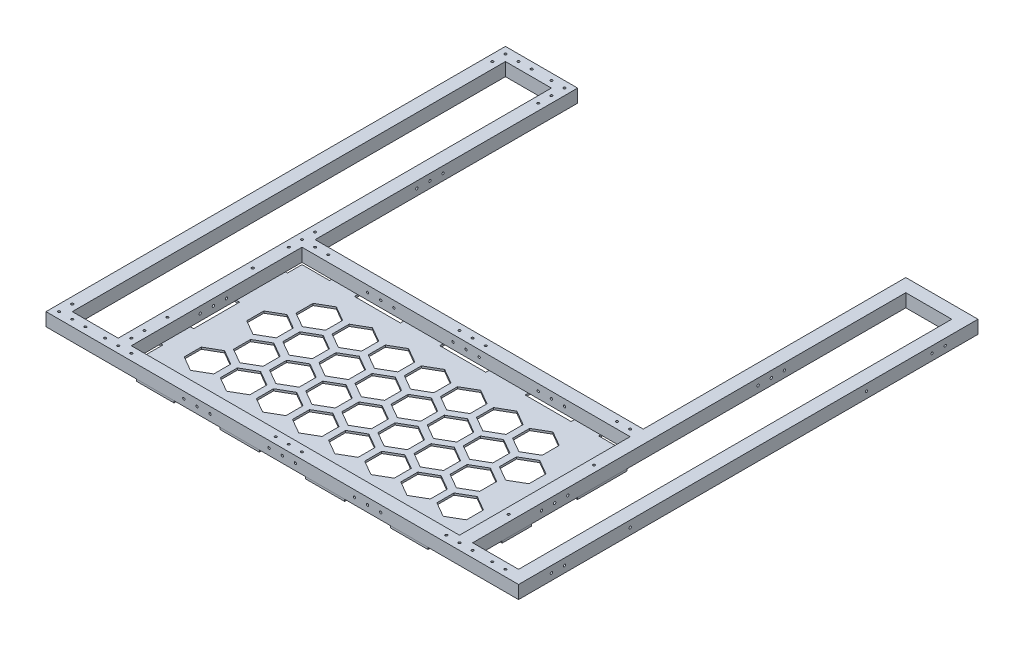
SolidWorks part; units mm, degrees
ref_plane "前视基准面" through (0, 0, 0) normal (0, 0, 1) x (1, 0, 0)
ref_plane "上视基准面" through (0, 0, 0) normal (0, 1, 0) x (1, 0, 0)
ref_plane "右视基准面" through (0, 0, 0) normal (1, 0, 0) x (0, 0, -1)
sketch "草图1" plane through (0, 0, 0) normal (0, 1, 0) x (1, 0, 0)
  line L0 (0, 0) -> (0, 100.2778) construction
  line L1 (250, 10) -> (-250, 10)
  line L2 (250, 10) -> (250, -10)
  line L3 (250, -10) -> (-250, -10)
  line L4 (-250, 10) -> (-250, -10)
  line L5 (250, 10) -> (-250, -10) construction
  line L6 (250, -10) -> (-250, 10) construction
  line L7 (360, 390) -> (250, 390)
  line L8 (-360, -270) -> (360, -270)
  line L9 (-360, -270) -> (-360, -290)
  line L10 (-360, -290) -> (360, -290)
  line L11 (360, -270) -> (360, -290)
  line L12 (-340, -270) -> (-360, -270)
  line L13 (-340, -270) -> (-340, 390)
  line L14 (-340, 390) -> (-360, 390)
  line L15 (-360, -270) -> (-360, 390)
  line L16 (-360, 410) -> (-250, 410)
  line L17 (-360, 410) -> (-360, 390)
  line L18 (-360, 390) -> (-250, 390)
  line L19 (-250, 410) -> (-250, 390)
  line L20 (-270, 390) -> (-250, 390)
  line L21 (-270, 390) -> (-270, -270)
  line L22 (-270, -270) -> (-250, -270)
  line L23 (-250, 390) -> (-250, -270)
  line L24 (250, 410) -> (250, 390)
  line L25 (340, -270) -> (360, -270)
  line L26 (360, 410) -> (250, 410)
  line L31 (270, -270) -> (250, -270)
  line L32 (250, 390) -> (250, -270)
  line L33 (270, 390) -> (250, 390)
  line L34 (270, 390) -> (270, -270)
  line L35 (360, 410) -> (360, 390)
  line L36 (340, 390) -> (360, 390)
  line L38 (340, -270) -> (360, -270)
  line L39 (340, 390) -> (360, 390)
  line L40 (340, 390) -> (340, -270)
  line L41 (340, -270) -> (360, -270)
  line L42 (360, 390) -> (360, -270)
  point P0 (0, 0)
  dimension "D1" = 20
  dimension "D2" = 20
  dimension "D3" = 20
  dimension "D4" = 20
  dimension "D5" = 20
  dimension "D6" = 110
  dimension "D7" = 700
  dimension "D8" = 720
  dimension "D9" = 400
extrude "凸台-拉伸1" add sketch "草图1" along normal blind 20 contours L23 L18 L21 L8 L4 | L19 L16 L17 L14 L18 | L15 L8 L13 L14 | L1 L4 L3 L2 | L11 L8 L9 L10 | L34 L7 L32 L2 L8 | L42 L7 L40 L8 | L35 L26 L24 L7
sketch "草图3" plane through (0, 0, 0) normal (0, -1, 0) x (1, 0, 0)
  line L0 (-360, 290) -> (360, 290) construction
  line L1 (-340, 270) -> (340, 270)
  line L2 (-340, 270) -> (-340, 290)
  line L3 (-340, 290) -> (340, 290)
  line L4 (340, 270) -> (340, 290)
  line L5 (340, -390) -> (340, 270) construction
  line L7 (340, 290) -> (360, 290)
  line L8 (340, 290) -> (340, -410)
  line L9 (340, -410) -> (360, -410)
  line L10 (360, 290) -> (360, -410)
  line L11 (-340, 290) -> (-360, 290)
  line L12 (-340, 290) -> (-340, -410)
  line L13 (-340, -410) -> (-360, -410)
  line L14 (-360, 290) -> (-360, -410)
  line L15 (-250, -410) -> (-340, -410)
  line L16 (-250, -410) -> (-250, -390)
  line L17 (-250, -390) -> (-340, -390)
  line L18 (-340, -410) -> (-340, -390)
  line L19 (250, -410) -> (340, -410)
  line L20 (250, -410) -> (250, -390)
  line L21 (250, -390) -> (340, -390)
  line L22 (340, -410) -> (340, -390)
  line L23 (270, 270) -> (250, 270)
  line L24 (270, 270) -> (270, -390)
  line L25 (270, -390) -> (250, -390)
  line L26 (250, 270) -> (250, -390)
  line L27 (-250, 270) -> (-270, 270)
  line L28 (-250, 270) -> (-250, -390)
  line L29 (-250, -390) -> (-270, -390)
  line L30 (-270, 270) -> (-270, -390)
  line L31 (-250, 10) -> (250, 10)
  line L32 (-250, 10) -> (-250, -10)
  line L33 (-250, -10) -> (250, -10)
  line L34 (250, 10) -> (250, -10)
  line L35 (0, 0) -> (0, -76.2927) construction
  circle A0 centre (240, 0) radius 1.75
  circle A1 centre (220, 0) radius 1.75
  circle A2 centre (-220, 0) radius 1.75
  circle A3 centre (-240, 0) radius 1.75
  circle A4 centre (-330, 280) radius 1.75
  circle A5 centre (-310, 280) radius 1.75
  circle A6 centre (310, 280) radius 1.75
  circle A7 centre (330, 280) radius 1.75
  circle A8 centre (-260, 280) radius 1.75
  circle A9 centre (-240, 280) radius 1.75
  circle A10 centre (-280, 280) radius 1.75
  circle A11 centre (240, 280) radius 1.75
  circle A12 centre (260, 280) radius 1.75
  circle A13 centre (280, 280) radius 1.75
  circle A14 centre (-350, 280) radius 1.75
  circle A15 centre (-350, 260) radius 1.75
  circle A16 centre (-350, -400) radius 1.75
  circle A17 centre (-350, -380) radius 1.75
  circle A18 centre (-330, -400) radius 1.75
  circle A19 centre (-310, -400) radius 1.75
  circle A20 centre (-280, -400) radius 1.75
  circle A21 centre (-260, -400) radius 1.75
  circle A22 centre (-260, 260) radius 1.75
  circle A23 centre (-260, 240) radius 1.75
  circle A24 centre (-260, 0) radius 1.75
  circle A25 centre (-260, 20) radius 1.75
  circle A26 centre (-260, -20) radius 1.75
  circle A27 centre (-260, -380) radius 1.75
  circle A28 centre (-260, -360) radius 1.75
  dimension "D1" = 20
  dimension "D4" = 3.5
  dimension "D5" = 10
  dimension "D6" = 3.5
  dimension "D9" = 3.5
  dimension "D14" = 3.5
  dimension "D15" = 10
  dimension "D20" = 10
  dimension "D25" = 3.5
  dimension "D26" = 10
  dimension "D27" = 3.5
  dimension "D2" = 10
  dimension "D3" = 10
  dimension "D7" = 10
  dimension "D8" = 20
  dimension "D10" = 10
  dimension "D11" = 20
  dimension "D12" = 20
  dimension "D13" = 10
  dimension "D16" = 20
  dimension "D17" = 10
  dimension "D18" = 20
  dimension "D19" = 10
  dimension "D21" = 10
  dimension "D22" = 20
  dimension "D23" = 20
  dimension "D24" = 10
  dimension "D28" = 10
  dimension "D29" = 20
  dimension "D30" = 20
  dimension "D31" = 20
  dimension "D32" = 10
  dimension "D33" = 20
  dimension "D34" = 20
sketch "草图4" plane through (360, 0, 0) normal (1, 0, 0) x (0, 0, -1)
  line L0 (-270, 0) -> (390, 0) construction
  line L1 (410, 20) -> (410, 0) construction
  line L2 (-290, 20) -> (-290, 0) construction
  line L7 (-290, 0) -> (410, 0)
  line L8 (410, 0) -> (410, 20)
  line L9 (410, 20) -> (-290, 20)
  line L10 (-290, 20) -> (-290, 0)
  line L11 (-290, 0) -> (410, 0)
  line L12 (410, 0) -> (410, 20)
  line L13 (410, 20) -> (-290, 20)
  line L14 (-290, 20) -> (-290, 0)
  circle A0 centre (-240, 10) radius 1.75
  circle A1 centre (-220, 10) radius 1.75
  circle A2 centre (-120, 10) radius 1.75
  circle A3 centre (360, 10) radius 1.75
  circle A4 centre (340, 10) radius 1.75
  circle A5 centre (240, 10) radius 1.75
  dimension "D1" = 10
  dimension "D8" = 3.5
  dimension "D2" = 50
  dimension "D3" = 20
  dimension "D4" = 100
  dimension "D5" = 50
  dimension "D6" = 20
  dimension "D7" = 100
  dimension "D9" = 0
extrude "切除-拉伸1" cut sketch "草图3" against normal up to next (20 mm away) contours A4 | A5 | A15 | A17 | A18 | A19 | A20 | A28 | A8 | A9 | A10 | A22 | A23 | A25 | A24 | A26 | A3 | A2 | A0 | A1 | A11 | A13 | A7 | A6 | A14 | A16 | A21 | A27 | A12
extrude "切除-拉伸2" cut sketch "草图4" against normal up to next contours A0 | A1 | A2 | A5 | A4 | A3
sketch "草图5" plane through (270, 0, 0) normal (1, 0, 0) x (0, 0, -1)
  line L0 (410, 20) -> (410, 0) construction
  line L1 (410, 20) -> (410, 0)
  line L3 (390, 20) -> (-270, 20) construction
  line L4 (-290, 20) -> (-290, 0) construction
  line L5 (-290, 20) -> (-290, 0)
  circle A0 centre (185, 10) radius 1.75
  circle A1 centre (165, 10) radius 1.75
  circle A2 centre (205, 10) radius 1.75
  circle A3 centre (-165, 10) radius 1.75
  circle A4 centre (-145, 10) radius 1.75
  circle A5 centre (-125, 10) radius 1.75
  dimension "D1" = 225
  dimension "D8" = 3.5
  dimension "D2" = 20
  dimension "D3" = 20
  dimension "D4" = 20
  dimension "D5" = 20
  dimension "D6" = 10
  dimension "D7" = 145
extrude "切除-拉伸3" cut sketch "草图5" against normal up to next contours A1 | A0 | A2 | A5 | A4 | A3
sketch "草图6" plane through (-250, 0, 0) normal (1, 0, 0) x (0, 0, -1)
  circle A0 centre (205, 10) radius 1.75 construction
  circle A1 centre (185, 10) radius 1.75 construction
  circle A2 centre (165, 10) radius 1.75 construction
  circle A3 centre (-165, 10) radius 1.75 construction
  circle A4 centre (-145, 10) radius 1.75 construction
  circle A5 centre (-125, 10) radius 1.75 construction
  circle A6 centre (205, 10) radius 1.75
  circle A7 centre (185, 10) radius 1.75
  circle A8 centre (165, 10) radius 1.75
  circle A9 centre (-165, 10) radius 1.75
  circle A10 centre (-145, 10) radius 1.75
  circle A11 centre (-125, 10) radius 1.75
extrude "切除-拉伸4" cut sketch "草图6" against normal up to next
sketch "草图7" plane through (0, 0, 10) normal (0, 0, 1) x (1, 0, 0)
  line L0 (250, 20) -> (-250, 20) construction
  circle A0 centre (0, 10) radius 1.75
  circle A1 centre (20, 10) radius 1.75
  circle A2 centre (-20, 10) radius 1.75
  circle A3 centre (110, 10) radius 1.75
  circle A4 centre (130, 10) radius 1.75
  circle A5 centre (150, 10) radius 1.75
  circle A6 centre (-110, 10) radius 1.75
  circle A7 centre (-130, 10) radius 1.75
  circle A8 centre (-150, 10) radius 1.75
  dimension "D1" = 20
  dimension "D7" = 3.5
  dimension "D2" = 20
  dimension "D3" = 20
  dimension "D4" = 20
  dimension "D5" = 20
  dimension "D6" = 20
  dimension "D8" = 10
  dimension "D9" = 130
  dimension "D10" = 130
extrude "切除-拉伸5" cut sketch "草图7" against normal blind 20
sketch "草图8" plane through (0, 0, 290) normal (0, 0, 1) x (1, 0, 0)
  circle A1 centre (-130, 10) radius 1.75
  circle A2 centre (-130, 10) radius 1.75
  circle A3 centre (-110, 10) radius 1.75
  circle A4 centre (-110, 10) radius 1.75
  circle A5 centre (150, 10) radius 1.75
  circle A6 centre (150, 10) radius 1.75
  circle A7 centre (130, 10) radius 1.75
  circle A8 centre (130, 10) radius 1.75
  circle A9 centre (110, 10) radius 1.75
  circle A10 centre (110, 10) radius 1.75
  circle A11 centre (-20, 10) radius 1.75
  circle A12 centre (-20, 10) radius 1.75
  circle A13 centre (20, 10) radius 1.75
  circle A14 centre (20, 10) radius 1.75
  circle A15 centre (0, 10) radius 1.75
  circle A16 centre (0, 10) radius 1.75
  circle A17 centre (-150, 10) radius 1.75
  circle A18 centre (-150, 10) radius 1.75
  dimension "D1" = 0
  dimension "D2" = 0
  dimension "D3" = 0
  dimension "D4" = 0
  dimension "D5" = 0
  dimension "D6" = 0
  dimension "D7" = 0
  dimension "D8" = 0
  dimension "D9" = 0
extrude "切除-拉伸6" cut sketch "草图8" against normal blind 20
sketch "草图9" plane through (0, 20, 0) normal (0, 1, 0) x (1, 0, 0)
  line L0 (250, 10) -> (-250, -10) construction
  circle A0 centre (0, 0) radius 1.75
  circle A1 centre (20, 0) radius 1.75
  circle A2 centre (-20, 0) radius 1.75
  dimension "D1" = 3.5
  dimension "D4" = 20
  dimension "D5" = 20
  dimension "D2" = 2
  dimension "D3" = 2
extrude "切除-拉伸7" cut sketch "草图9" against normal blind 20
sketch "草图10" plane through (0, 20, 0) normal (0, 1, 0) x (1, 0, 0)
  line L0 (0, 0) -> (0, -280) construction
  line L1 (250, -10) -> (-250, 10) construction
  line L2 (-360, -270) -> (360, -270) construction
  line L3 (0, -280) -> (-20, -280) construction
  circle A0 centre (0, -280) radius 1.75
  circle A1 centre (20, -280) radius 1.75
  circle A2 centre (-20, -280) radius 1.75
  dimension "D1" = 3.5
  dimension "D2" = 10
  dimension "D5" = 20
  dimension "D6" = 20
  dimension "D3" = 2
  dimension "D4" = 2
extrude "切除-拉伸8" cut sketch "草图10" against normal blind 20
sketch "草图11" plane through (0, 20, 0) normal (0, 1, 0) x (1, 0, 0)
  line L0 (-270, 390) -> (-270, -270) construction
  line L1 (-360, -290) -> (360, -290) construction
  line L2 (0, 0) -> (0, -95.7214) construction
  circle A0 centre (-260, -75) radius 1.75
  circle A1 centre (-260, -205) radius 1.75
  circle A2 centre (260, -205) radius 1.75
  circle A3 centre (260, -75) radius 1.75
  dimension "D1" = 10
  dimension "D2" = 3.5
  dimension "D3" = 85
  dimension "D4" = 130
extrude "切除-拉伸9" cut sketch "草图11" against normal blind 20
sketch "草图14" plane through (0, 0, 0) normal (0, -1, 0) x (1, 0, 0)
  line L1 (360, -410) -> (-360, -410)
  line L2 (360, -410) -> (360, 270)
  line L3 (360, 270) -> (-360, 270)
  line L4 (-360, -410) -> (-360, 270)
sketch "草图15" plane through (0, 0, 0) normal (0, -1, 0) x (1, 0, 0)
  line L1 (-360, 290) -> (360, 290)
  line L2 (-360, 290) -> (-360, -410)
  line L3 (-360, -410) -> (360, -410)
  line L4 (360, 290) -> (360, -410)
  line L5 (-250, 10) -> (250, 10)
  line L6 (-250, 10) -> (-250, -10)
  line L7 (-250, -10) -> (250, -10)
  line L8 (250, 10) -> (250, -10)
sketch "草图16" plane through (0, 0, 0) normal (0, -1, 0) x (1, 0, 0)
  line L1 (-270, -390) -> (-270, 270) construction
  line L2 (-270, 225) -> (-247, 225)
  line L3 (-250, -390) -> (-250, 270) construction
  line L4 (-247, 225) -> (-247, 267)
  line L5 (-247, 267) -> (-222, 267)
  line L6 (-360, 270) -> (360, 270) construction
  line L7 (-222, 267) -> (-222, 290)
  line L8 (-360, 290) -> (360, 290) construction
  line L10 (-35, 290) -> (-35, 265)
  line L12 (35, 265) -> (35, 290)
  line L14 (222, 290) -> (222, 267)
  line L15 (222, 267) -> (247, 267)
  line L16 (247, 267) -> (247, 225)
  line L18 (247, 225) -> (270, 225)
  line L19 (270, -390) -> (270, 270) construction
  line L21 (270, 35) -> (247, 35)
  line L24 (250, 10) -> (-250, 10) construction
  line L25 (205, 13) -> (205, -10)
  line L29 (35, -10) -> (35, 15)
  line L30 (35, 15) -> (-35, 15)
  line L31 (-35, 15) -> (-35, -10)
  line L33 (-205, -10) -> (-205, 13)
  line L36 (-247, 35) -> (-270, 35)
  line L37 (250, -10) -> (-250, -10) construction
  line L38 (0, 0) -> (0, 103.7816) construction
  line L39 (-35, -10) -> (-95, -10)
  line L40 (-95, -10) -> (-95, 15)
  line L41 (-95, 15) -> (-165, 15)
  line L42 (-165, 15) -> (-165, -10)
  line L43 (-165, -10) -> (-205, -10)
  line L44 (205, -10) -> (165, -10)
  line L45 (165, -10) -> (165, 15)
  line L46 (165, 15) -> (95, 15)
  line L47 (95, 15) -> (95, -10)
  line L48 (95, -10) -> (35, -10)
  line L49 (0, 0) -> (0, -100.2778) construction
  line L50 (270, 225) -> (270, 180)
  line L51 (-270, 225) -> (-270, 180)
  line L52 (-270, 180) -> (-245, 180)
  line L53 (-245, 180) -> (-245, 110)
  line L54 (-245, 110) -> (-270, 110)
  line L55 (-270, 110) -> (-270, 35)
  line L56 (270, 180) -> (245, 180)
  line L57 (245, 180) -> (245, 110)
  line L58 (245, 110) -> (270, 110)
  line L59 (270, 110) -> (270, 35)
  line L60 (-222, 290) -> (-165, 290)
  line L61 (-165, 290) -> (-165, 265)
  line L62 (-165, 265) -> (-95, 265)
  line L63 (-95, 265) -> (-95, 290)
  line L64 (-95, 290) -> (-35, 290)
  line L65 (35, 290) -> (95, 290)
  line L66 (95, 290) -> (95, 265)
  line L67 (95, 265) -> (165, 265)
  line L68 (165, 265) -> (165, 290)
  line L69 (165, 290) -> (222, 290)
  line L70 (-35, 265) -> (35, 265)
  line L71 (-247, 35) -> (-247, 13)
  line L72 (-247, 13) -> (-205, 13)
  line L73 (247, 35) -> (247, 13)
  line L74 (247, 13) -> (205, 13)
  dimension "D2" = 35
  dimension "D3" = 45
  dimension "D4" = 25
  dimension "D5" = 95
  dimension "D6" = 70
  dimension "D7" = 5
  dimension "D8" = 5
  dimension "D9" = 45
  dimension "D10" = 70
  dimension "D11" = 70
  dimension "D12" = 70
  dimension "D13" = 70
  dimension "D14" = 25
  dimension "D15" = 130
  dimension "D16" = 110
  dimension "D17" = 3
  dimension "D18" = 3
  dimension "D19" = 3
  dimension "D20" = 3
  dimension "D21" = 5
extrude "凸台-拉伸7" add sketch "草图16" along normal blind 3 separate body
sketch "草图17" plane through (0, -3, 0) normal (0, -1, 0) x (1, 0, 0)
  circle A0 centre (260, 75) radius 1.75 construction
  circle A1 centre (260, 205) radius 1.75 construction
  circle A2 centre (-260, 75) radius 1.75 construction
  circle A3 centre (-260, 205) radius 1.75 construction
  circle A4 centre (260, 75) radius 1.75 construction
  circle A5 centre (260, 205) radius 1.75 construction
  circle A6 centre (-260, 75) radius 1.75 construction
  circle A7 centre (-260, 205) radius 1.75 construction
  circle A8 centre (-260, 205) radius 2
  circle A9 centre (-260, 75) radius 2
  circle A10 centre (260, 205) radius 2
  circle A11 centre (260, 75) radius 2
  dimension "D1" = 4
extrude "切除-拉伸10" cut sketch "草图17" against normal blind 3
sketch "草图19" plane through (0, -3, 0) normal (0, -1, 0) x (1, 0, 0)
  line L1 (-302.5, 185.4663) -> (-280, 198.4567)
  line L2 (-280, 198.4567) -> (-280, 224.4375)
  line L3 (-280, 224.4375) -> (-302.5, 237.4279)
  line L4 (-302.5, 237.4279) -> (-325, 224.4375)
  line L5 (-325, 224.4375) -> (-325, 198.4567)
  line L6 (-325, 198.4567) -> (-302.5, 185.4663)
  line L12 (-192.5, 185.4663) -> (-170, 198.4567)
  line L13 (-170, 198.4567) -> (-170, 224.4375)
  line L14 (-170, 224.4375) -> (-192.5, 237.4279)
  line L15 (-192.5, 237.4279) -> (-215, 224.4375)
  line L16 (-215, 224.4375) -> (-215, 198.4567)
  line L17 (-215, 198.4567) -> (-192.5, 185.4663)
  line L18 (-137.5, 185.4663) -> (-115, 198.4567)
  line L19 (-115, 198.4567) -> (-115, 224.4375)
  line L20 (-115, 224.4375) -> (-137.5, 237.4279)
  line L21 (-137.5, 237.4279) -> (-160, 224.4375)
  line L22 (-160, 224.4375) -> (-160, 198.4567)
  line L23 (-160, 198.4567) -> (-137.5, 185.4663)
  line L24 (-82.5, 185.4663) -> (-60, 198.4567)
  line L25 (-60, 198.4567) -> (-60, 224.4375)
  line L26 (-60, 224.4375) -> (-82.5, 237.4279)
  line L27 (-82.5, 237.4279) -> (-105, 224.4375)
  line L28 (-105, 224.4375) -> (-105, 198.4567)
  line L29 (-105, 198.4567) -> (-82.5, 185.4663)
  line L30 (-27.5, 185.4663) -> (-5, 198.4567)
  line L31 (-5, 198.4567) -> (-5, 224.4375)
  line L32 (-5, 224.4375) -> (-27.5, 237.4279)
  line L33 (-27.5, 237.4279) -> (-50, 224.4375)
  line L34 (-50, 224.4375) -> (-50, 198.4567)
  line L35 (-50, 198.4567) -> (-27.5, 185.4663)
  line L36 (27.5, 185.4663) -> (50, 198.4567)
  line L37 (50, 198.4567) -> (50, 224.4375)
  line L38 (50, 224.4375) -> (27.5, 237.4279)
  line L39 (27.5, 237.4279) -> (5, 224.4375)
  line L40 (5, 224.4375) -> (5, 198.4567)
  line L41 (5, 198.4567) -> (27.5, 185.4663)
  line L42 (82.5, 185.4663) -> (105, 198.4567)
  line L43 (105, 198.4567) -> (105, 224.4375)
  line L44 (105, 224.4375) -> (82.5, 237.4279)
  line L45 (82.5, 237.4279) -> (60, 224.4375)
  line L46 (60, 224.4375) -> (60, 198.4567)
  line L47 (60, 198.4567) -> (82.5, 185.4663)
  line L48 (137.5, 185.4663) -> (160, 198.4567)
  line L49 (160, 198.4567) -> (160, 224.4375)
  line L50 (160, 224.4375) -> (137.5, 237.4279)
  line L51 (137.5, 237.4279) -> (115, 224.4375)
  line L52 (115, 224.4375) -> (115, 198.4567)
  line L53 (115, 198.4567) -> (137.5, 185.4663)
  line L54 (192.5, 185.4663) -> (215, 198.4567)
  line L55 (215, 198.4567) -> (215, 224.4375)
  line L56 (215, 224.4375) -> (192.5, 237.4279)
  line L57 (192.5, 237.4279) -> (170, 224.4375)
  line L58 (170, 224.4375) -> (170, 198.4567)
  line L59 (170, 198.4567) -> (192.5, 185.4663)
  line L66 (-165, 137.8349) -> (-142.5, 150.8253)
  line L67 (-142.5, 150.8253) -> (-142.5, 176.8061)
  line L68 (-142.5, 176.8061) -> (-165, 189.7965)
  line L69 (-165, 189.7965) -> (-187.5, 176.8061)
  line L70 (-187.5, 176.8061) -> (-187.5, 150.8253)
  line L71 (-187.5, 150.8253) -> (-165, 137.8349)
  line L72 (-110, 137.8349) -> (-87.5, 150.8253)
  line L73 (-87.5, 150.8253) -> (-87.5, 176.8061)
  line L74 (-87.5, 176.8061) -> (-110, 189.7965)
  line L75 (-110, 189.7965) -> (-132.5, 176.8061)
  line L76 (-132.5, 176.8061) -> (-132.5, 150.8253)
  line L77 (-132.5, 150.8253) -> (-110, 137.8349)
  line L78 (-55, 137.8349) -> (-32.5, 150.8253)
  line L79 (-32.5, 150.8253) -> (-32.5, 176.8061)
  line L80 (-32.5, 176.8061) -> (-55, 189.7965)
  line L81 (-55, 189.7965) -> (-77.5, 176.8061)
  line L82 (-77.5, 176.8061) -> (-77.5, 150.8253)
  line L83 (-77.5, 150.8253) -> (-55, 137.8349)
  line L84 (0, 137.8349) -> (22.5, 150.8253)
  line L85 (22.5, 150.8253) -> (22.5, 176.8061)
  line L86 (22.5, 176.8061) -> (0, 189.7965)
  line L87 (0, 189.7965) -> (-22.5, 176.8061)
  line L88 (-22.5, 176.8061) -> (-22.5, 150.8253)
  line L89 (-22.5, 150.8253) -> (0, 137.8349)
  line L90 (55, 137.8349) -> (77.5, 150.8253)
  line L91 (77.5, 150.8253) -> (77.5, 176.8061)
  line L92 (77.5, 176.8061) -> (55, 189.7965)
  line L93 (55, 189.7965) -> (32.5, 176.8061)
  line L94 (32.5, 176.8061) -> (32.5, 150.8253)
  line L95 (32.5, 150.8253) -> (55, 137.8349)
  line L96 (110, 137.8349) -> (132.5, 150.8253)
  line L97 (132.5, 150.8253) -> (132.5, 176.8061)
  line L98 (132.5, 176.8061) -> (110, 189.7965)
  line L99 (110, 189.7965) -> (87.5, 176.8061)
  line L100 (87.5, 176.8061) -> (87.5, 150.8253)
  line L101 (87.5, 150.8253) -> (110, 137.8349)
  line L102 (165, 137.8349) -> (187.5, 150.8253)
  line L103 (187.5, 150.8253) -> (187.5, 176.8061)
  line L104 (187.5, 176.8061) -> (165, 189.7965)
  line L105 (165, 189.7965) -> (142.5, 176.8061)
  line L106 (142.5, 176.8061) -> (142.5, 150.8253)
  line L107 (142.5, 150.8253) -> (165, 137.8349)
  line L114 (-192.5, 90.2035) -> (-170, 103.1939)
  line L115 (-170, 103.1939) -> (-170, 129.1747)
  line L116 (-170, 129.1747) -> (-192.5, 142.1651)
  line L117 (-192.5, 142.1651) -> (-215, 129.1747)
  line L118 (-215, 129.1747) -> (-215, 103.1939)
  line L119 (-215, 103.1939) -> (-192.5, 90.2035)
  line L120 (-137.5, 90.2035) -> (-115, 103.1939)
  line L121 (-115, 103.1939) -> (-115, 129.1747)
  line L122 (-115, 129.1747) -> (-137.5, 142.1651)
  line L123 (-137.5, 142.1651) -> (-160, 129.1747)
  line L124 (-160, 129.1747) -> (-160, 103.1939)
  line L125 (-160, 103.1939) -> (-137.5, 90.2035)
  line L126 (-82.5, 90.2035) -> (-60, 103.1939)
  line L127 (-60, 103.1939) -> (-60, 129.1747)
  line L128 (-60, 129.1747) -> (-82.5, 142.1651)
  line L129 (-82.5, 142.1651) -> (-105, 129.1747)
  line L130 (-105, 129.1747) -> (-105, 103.1939)
  line L131 (-105, 103.1939) -> (-82.5, 90.2035)
  line L132 (-27.5, 90.2035) -> (-5, 103.1939)
  line L133 (-5, 103.1939) -> (-5, 129.1747)
  line L134 (-5, 129.1747) -> (-27.5, 142.1651)
  line L135 (-27.5, 142.1651) -> (-50, 129.1747)
  line L136 (-50, 129.1747) -> (-50, 103.1939)
  line L137 (-50, 103.1939) -> (-27.5, 90.2035)
  line L138 (27.5, 90.2035) -> (50, 103.1939)
  line L139 (50, 103.1939) -> (50, 129.1747)
  line L140 (50, 129.1747) -> (27.5, 142.1651)
  line L141 (27.5, 142.1651) -> (5, 129.1747)
  line L142 (5, 129.1747) -> (5, 103.1939)
  line L143 (5, 103.1939) -> (27.5, 90.2035)
  line L144 (82.5, 90.2035) -> (105, 103.1939)
  line L145 (105, 103.1939) -> (105, 129.1747)
  line L146 (105, 129.1747) -> (82.5, 142.1651)
  line L147 (82.5, 142.1651) -> (60, 129.1747)
  line L148 (60, 129.1747) -> (60, 103.1939)
  line L149 (60, 103.1939) -> (82.5, 90.2035)
  line L150 (137.5, 90.2035) -> (160, 103.1939)
  line L151 (160, 103.1939) -> (160, 129.1747)
  line L152 (160, 129.1747) -> (137.5, 142.1651)
  line L153 (137.5, 142.1651) -> (115, 129.1747)
  line L154 (115, 129.1747) -> (115, 103.1939)
  line L155 (115, 103.1939) -> (137.5, 90.2035)
  line L156 (192.5, 90.2035) -> (215, 103.1939)
  line L157 (215, 103.1939) -> (215, 129.1747)
  line L158 (215, 129.1747) -> (192.5, 142.1651)
  line L159 (192.5, 142.1651) -> (170, 129.1747)
  line L160 (170, 129.1747) -> (170, 103.1939)
  line L161 (170, 103.1939) -> (192.5, 90.2035)
  line L168 (-165, 42.5721) -> (-142.5, 55.5625)
  line L169 (-142.5, 55.5625) -> (-142.5, 81.5433)
  line L170 (-142.5, 81.5433) -> (-165, 94.5337)
  line L171 (-165, 94.5337) -> (-187.5, 81.5433)
  line L172 (-187.5, 81.5433) -> (-187.5, 55.5625)
  line L173 (-187.5, 55.5625) -> (-165, 42.5721)
  line L174 (-110, 42.5721) -> (-87.5, 55.5625)
  line L175 (-87.5, 55.5625) -> (-87.5, 81.5433)
  line L176 (-87.5, 81.5433) -> (-110, 94.5337)
  line L177 (-110, 94.5337) -> (-132.5, 81.5433)
  line L178 (-132.5, 81.5433) -> (-132.5, 55.5625)
  line L179 (-132.5, 55.5625) -> (-110, 42.5721)
  line L180 (-55, 42.5721) -> (-32.5, 55.5625)
  line L181 (-32.5, 55.5625) -> (-32.5, 81.5433)
  line L182 (-32.5, 81.5433) -> (-55, 94.5337)
  line L183 (-55, 94.5337) -> (-77.5, 81.5433)
  line L184 (-77.5, 81.5433) -> (-77.5, 55.5625)
  line L185 (-77.5, 55.5625) -> (-55, 42.5721)
  line L186 (0, 42.5721) -> (22.5, 55.5625)
  line L187 (22.5, 55.5625) -> (22.5, 81.5433)
  line L188 (22.5, 81.5433) -> (0, 94.5337)
  line L189 (0, 94.5337) -> (-22.5, 81.5433)
  line L190 (-22.5, 81.5433) -> (-22.5, 55.5625)
  line L191 (-22.5, 55.5625) -> (0, 42.5721)
  line L192 (55, 42.5721) -> (77.5, 55.5625)
  line L193 (77.5, 55.5625) -> (77.5, 81.5433)
  line L194 (77.5, 81.5433) -> (55, 94.5337)
  line L195 (55, 94.5337) -> (32.5, 81.5433)
  line L196 (32.5, 81.5433) -> (32.5, 55.5625)
  line L197 (32.5, 55.5625) -> (55, 42.5721)
  line L198 (110, 42.5721) -> (132.5, 55.5625)
  line L199 (132.5, 55.5625) -> (132.5, 81.5433)
  line L200 (132.5, 81.5433) -> (110, 94.5337)
  line L201 (110, 94.5337) -> (87.5, 81.5433)
  line L202 (87.5, 81.5433) -> (87.5, 55.5625)
  line L203 (87.5, 55.5625) -> (110, 42.5721)
  line L204 (165, 42.5721) -> (187.5, 55.5625)
  line L205 (187.5, 55.5625) -> (187.5, 81.5433)
  line L206 (187.5, 81.5433) -> (165, 94.5337)
  line L207 (165, 94.5337) -> (142.5, 81.5433)
  line L208 (142.5, 81.5433) -> (142.5, 55.5625)
  line L209 (142.5, 55.5625) -> (165, 42.5721)
  line L240 (-302.5, 185.4663) -> (-247.5, 185.4663) construction
  line L242 (0, 0) -> (0, -69.0066) construction
  line L243 (27.5, 237.4279) -> (27.5, 265) construction
  line L244 (-220, 42.5721) -> (-197.5, 55.5625) [skipped]
  line L245 (-197.5, 55.5625) -> (-197.5, 81.5433) [skipped]
  line L246 (-197.5, 81.5433) -> (-220, 94.5337) [skipped]
  line L247 (-220, 94.5337) -> (-242.5, 81.5433) [skipped]
  line L248 (-242.5, 81.5433) -> (-242.5, 55.5625) [skipped]
  line L249 (-242.5, 55.5625) -> (-220, 42.5721) [skipped]
  line L250 (-247.5, 90.2035) -> (-225, 103.1939) [skipped]
  line L251 (-225, 103.1939) -> (-225, 129.1747) [skipped]
  line L252 (-225, 129.1747) -> (-247.5, 142.1651) [skipped]
  line L253 (-247.5, 142.1651) -> (-270, 129.1747) [skipped]
  line L254 (-270, 129.1747) -> (-270, 103.1939) [skipped]
  line L255 (-270, 103.1939) -> (-247.5, 90.2035) [skipped]
  line L256 (275, 42.5721) -> (297.5, 55.5625) [skipped]
  line L257 (297.5, 55.5625) -> (297.5, 81.5433) [skipped]
  line L258 (297.5, 81.5433) -> (275, 94.5337) [skipped]
  line L259 (275, 94.5337) -> (252.5, 81.5433) [skipped]
  line L260 (252.5, 81.5433) -> (252.5, 55.5625) [skipped]
  line L261 (252.5, 55.5625) -> (275, 42.5721) [skipped]
  line L262 (247.5, 90.2035) -> (270, 103.1939) [skipped]
  line L263 (270, 103.1939) -> (270, 129.1747) [skipped]
  line L264 (270, 129.1747) -> (247.5, 142.1651) [skipped]
  line L265 (247.5, 142.1651) -> (225, 129.1747) [skipped]
  line L266 (225, 129.1747) -> (225, 103.1939) [skipped]
  line L267 (225, 103.1939) -> (247.5, 90.2035) [skipped]
  line L268 (-220, 137.8349) -> (-197.5, 150.8253) [skipped]
  line L269 (-197.5, 150.8253) -> (-197.5, 176.8061) [skipped]
  line L270 (-197.5, 176.8061) -> (-220, 189.7965) [skipped]
  line L271 (-220, 189.7965) -> (-242.5, 176.8061) [skipped]
  line L272 (-242.5, 176.8061) -> (-242.5, 150.8253) [skipped]
  line L273 (-242.5, 150.8253) -> (-220, 137.8349) [skipped]
  line L274 (220, 137.8349) -> (242.5, 150.8253) [skipped]
  line L275 (242.5, 150.8253) -> (242.5, 176.8061) [skipped]
  line L276 (242.5, 176.8061) -> (220, 189.7965) [skipped]
  line L277 (220, 189.7965) -> (197.5, 176.8061) [skipped]
  line L278 (197.5, 176.8061) -> (197.5, 150.8253) [skipped]
  line L279 (197.5, 150.8253) -> (220, 137.8349) [skipped]
  line L280 (-247.5, 185.4663) -> (-225, 198.4567) [skipped]
  line L281 (-225, 198.4567) -> (-225, 224.4375) [skipped]
  line L282 (-225, 224.4375) -> (-247.5, 237.4279) [skipped]
  line L283 (-247.5, 237.4279) -> (-270, 224.4375) [skipped]
  line L284 (-270, 224.4375) -> (-270, 198.4567) [skipped]
  line L285 (-270, 198.4567) -> (-247.5, 185.4663) [skipped]
  line L286 (-275, 137.8349) -> (-252.5, 150.8253) [skipped]
  line L287 (-252.5, 150.8253) -> (-252.5, 176.8061) [skipped]
  line L288 (-252.5, 176.8061) -> (-275, 189.7965) [skipped]
  line L289 (-275, 189.7965) -> (-297.5, 176.8061) [skipped]
  line L290 (-297.5, 176.8061) -> (-297.5, 150.8253) [skipped]
  line L291 (-297.5, 150.8253) -> (-275, 137.8349) [skipped]
  line L292 (220, 42.5721) -> (242.5, 55.5625) [skipped]
  line L293 (242.5, 55.5625) -> (242.5, 81.5433) [skipped]
  line L294 (242.5, 81.5433) -> (220, 94.5337) [skipped]
  line L295 (220, 94.5337) -> (197.5, 81.5433) [skipped]
  line L296 (197.5, 81.5433) -> (197.5, 55.5625) [skipped]
  line L297 (197.5, 55.5625) -> (220, 42.5721) [skipped]
  line L298 (-35, 265) -> (35, 265) construction
  line L299 (35, 15) -> (-35, 15) construction
  line L300 (0, 42.5721) -> (0, 15) construction
  circle A0 centre (-302.5, 211.4471) radius 22.5 construction
  dimension "D1" = 45
  dimension "D4" = 55
  dimension "D5" = 10
  dimension "D6" = 10
  dimension "D7" = 10
  dimension "D2" = 10
  dimension "D3" = 4
extrude "切除-拉伸11" cut sketch "草图19" against normal blind 3 contours L16 L17 L12 L13 L14 L15 | L22 L23 L18 L19 L20 L21 | L28 L29 L24 L25 L26 L27 | L34 L35 L30 L31 L32 L33 | L40 L41 L36 L37 L38 L39 | L46 L47 L42 L43 L44 L45 | L52 L53 L48 L49 L50 L51 | L58 L59 L54 L55 L56 L57 | L106 L107 L102 L103 L104 L105 | L100 L101 L96 L97 L98 L99 | L94 L95 L90 L91 L92 L93 | L88 L89 L84 L85 L86 L87 | L82 L83 L78 L79 L80 L81 | L76 L77 L72 L73 L74 L75 | L70 L71 L66 L67 L68 L69 | L118 L119 L114 L115 L116 L117 | L124 L125 L120 L121 L122 L123 | L130 L131 L126 L127 L128 L129 | L136 L137 L132 L133 L134 L135 | L142 L143 L138 L139 L140 L141 | L148 L149 L144 L145 L146 L147 | L154 L155 L150 L151 L152 L153 | L160 L161 L156 L157 L158 L159 | L208 L209 L204 L205 L206 L207 | L202 L203 L198 L199 L200 L201 | L196 L197 L192 L193 L194 L195 | L190 L191 L186 L187 L188 L189 | L184 L185 L180 L181 L182 L183 | L178 L179 L174 L175 L176 L177 | L172 L173 L168 L169 L170 L171
